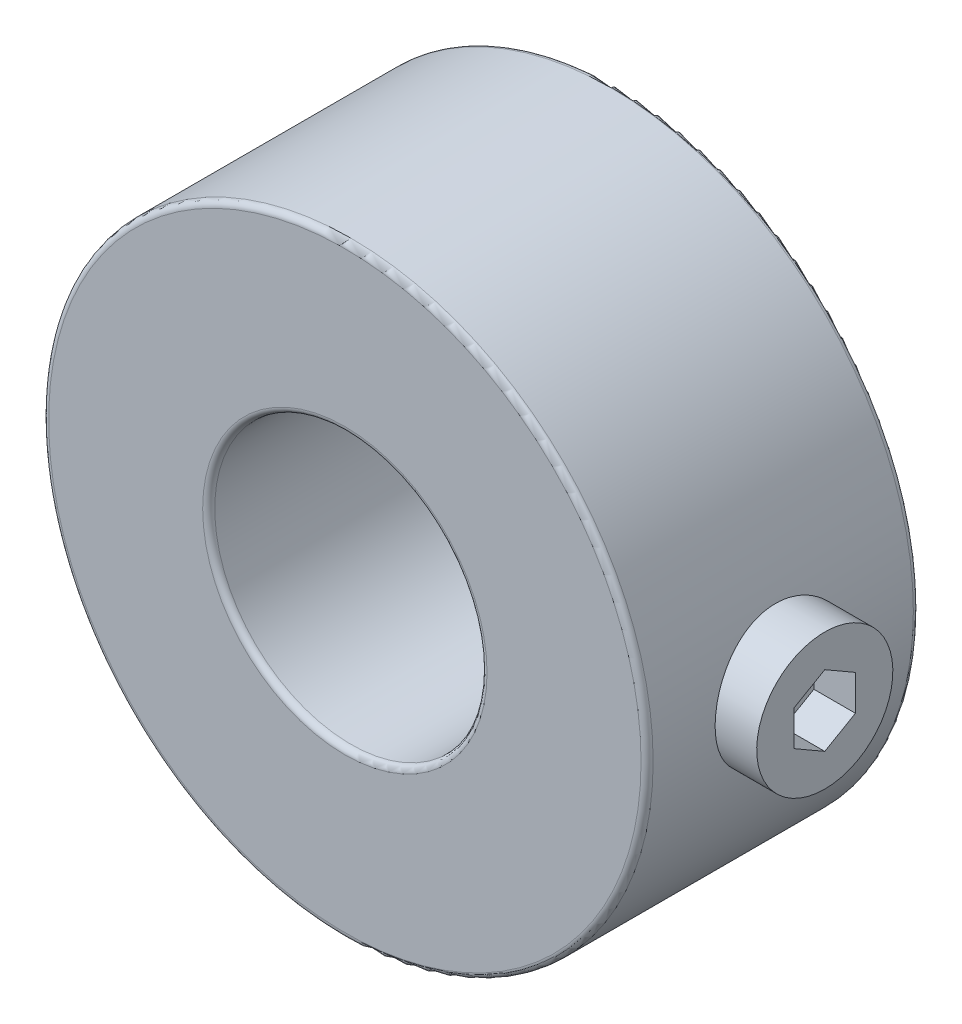
SolidWorks part; units mm, degrees
material "Cast Alloy Steel"
ref_plane "Front Plane" through (0, 0, 0) normal (0, 0, 1) x (1, 0, 0)
ref_plane "Top Plane" through (0, 0, 0) normal (0, 1, 0) x (1, 0, 0)
ref_plane "Right Plane" through (0, 0, 0) normal (1, 0, 0) x (0, 0, -1)
sketch "Sketch1" plane through (0, 0, 0) normal (0, 0, 1) x (1, 0, 0)
  circle A0 centre (0, 0) radius 11.1
  circle A1 centre (0, 0) radius 5
  point P4 (11.1, 0)
  dimension "Bore Dia" = 10
  dimension "OD" = 22.2
extrude "Extrude1" add sketch "Sketch1" along normal blind 10
ref_plane "Plane1" through (11.1, 0, 0) normal (1, 0, 0) x (0, 0, -1)
sketch "Sketch2" plane through (11.1, 0, 0) normal (1, 0, 0) x (0, 0, -1)
  line L0 (0, 0) -> (-10, 0) construction
  line L1 (-10, 11.1) -> (-10, -11.1) construction
  circle A0 centre (-5, 0) radius 2.5
  dimension "Set Screw Dia" = 5
extrude "Cut-Extrude1" cut sketch "Sketch2" against normal up to surface (11.1 mm away) up to plane "Right Plane"
ref_plane "Plane2" through (0, 0, 5) normal (0, 0, 1) x (1, 0, 0)
sketch "Sketch3" plane through (0, 0, 5) normal (0, 0, 1) x (1, 0, 0)
  line L1 (6.525, 0) -> (12.625, 0)
  line L2 (6.525, 0) -> (6.525, 2.5)
  line L3 (6.525, 2.5) -> (12.625, 2.5)
  line L4 (12.625, 0) -> (12.625, 2.5)
  line L5 (6.525, 0) -> (0, 0) construction
  dimension "D1" = 6.1
  dimension "D2" = 1.525
  dimension "D3" = 5
revolve "Revolve1" add sketch "Sketch3" angle 360 about L1
sketch "Sketch4" plane through (12.625, 0, 0) normal (1, 0, 0) x (0, 0, -1)
  line L1 (-5, 1.299) -> (-6.125, 0.6495)
  line L2 (-6.125, 0.6495) -> (-6.125, -0.6495)
  line L3 (-6.125, -0.6495) -> (-5, -1.299)
  line L4 (-5, -1.299) -> (-3.875, -0.6495)
  line L5 (-3.875, -0.6495) -> (-3.875, 0.6495)
  line L6 (-3.875, 0.6495) -> (-5, 1.299)
  circle A0 centre (-5, 0) radius 1.125 construction
  dimension "D1" = 2.25
extrude "Cut-Extrude2" cut sketch "Sketch4" against normal up to vertex (1.525 mm away) up to point (11.1, 0, 5)
fillet "Fillet1" radius 0.222 4 edges at (5, 0, 0) (5, 0, 10) (11.1, 0, 0) (11.1, 0, 10)
equation "\"D1@Sketch3\" = (\"OD@Sketch1\"-\"Bore Dia@Sketch1\")/2"
equation "\"D2@Sketch3\" = \"D1@Sketch3\"/4"
equation "\"D1@Sketch4\" = \"Set Screw Dia@Sketch2\"*.45"
equation "\"D3@Sketch3\" = \"Set Screw Dia@Sketch2\""
equation "\"D1@Fillet1\" = \"OD@Sketch1\"*.01"
